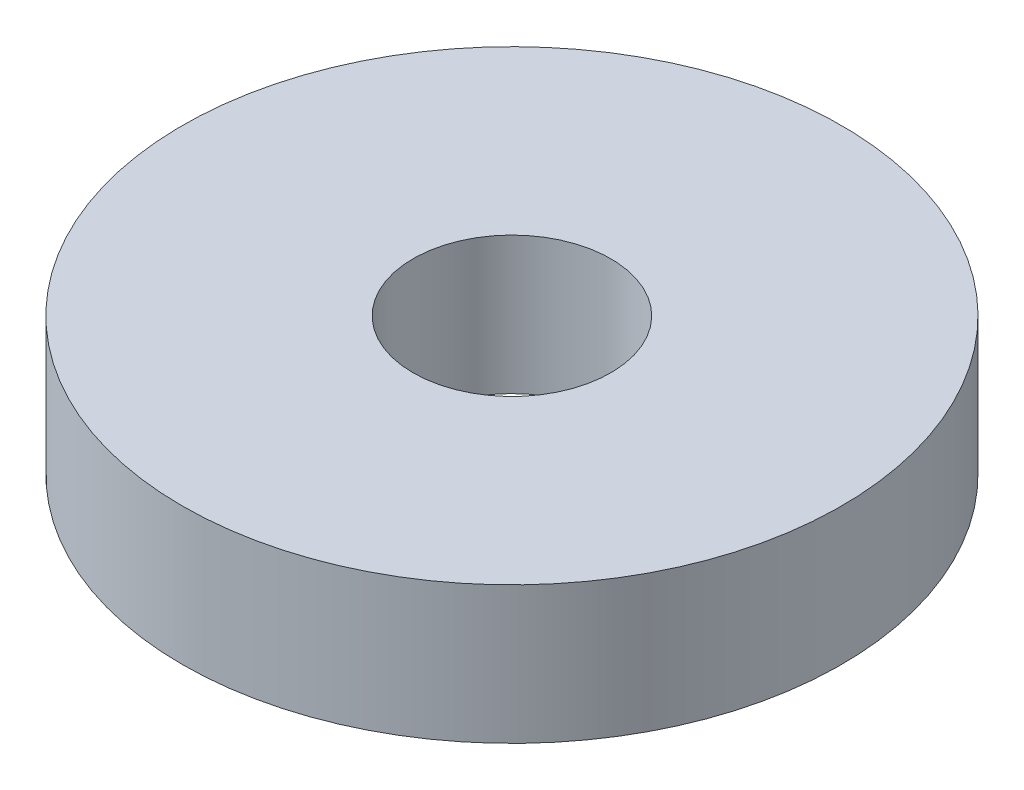
SolidWorks part; units mm, degrees
material "ABS"
ref_plane "前视基准面" through (0, 0, 0) normal (0, 0, 1) x (1, 0, 0)
ref_plane "上视基准面" through (0, 0, 0) normal (0, 1, 0) x (1, 0, 0)
ref_plane "右视基准面" through (0, 0, 0) normal (1, 0, 0) x (0, 0, -1)
other "Configuration Table"
sketch "草图1" plane through (0, 0, 0) normal (0, 1, 0) x (1, 0, 0)
  circle A0 centre (0, 0) radius 1.8
  circle A1 centre (0, 0) radius 6
  dimension "D1" = 3.6
  dimension "D2" = 12
extrude "凸台-拉伸1" add sketch "草图1" along normal blind 2.5
